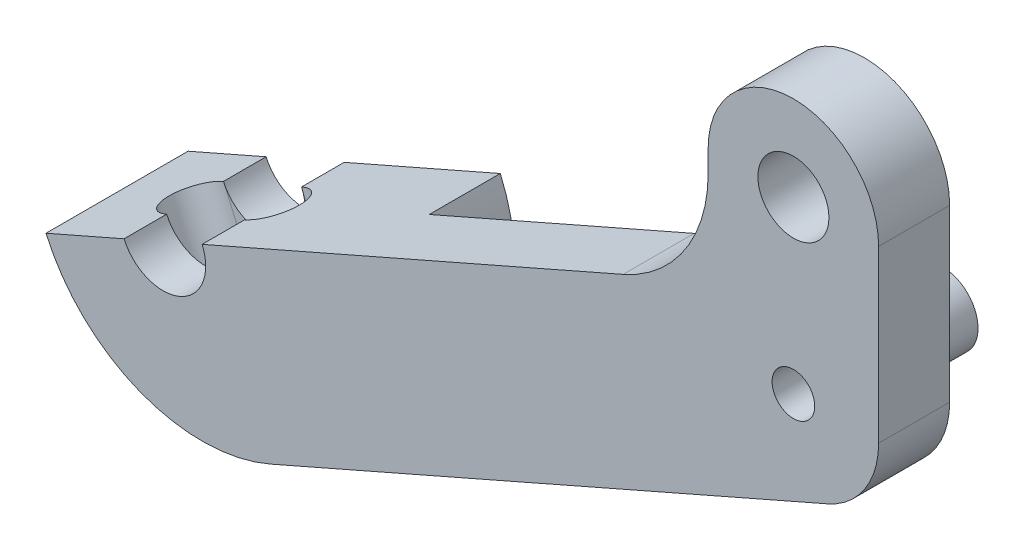
SolidWorks part; units mm, degrees
ref_plane "Plano frontal" through (0, 0, 0) normal (0, 0, 1) x (1, 0, 0)
ref_plane "Plano superior" through (0, 0, 0) normal (0, 1, 0) x (1, 0, 0)
ref_plane "Plano direito" through (0, 0, 0) normal (1, 0, 0) x (0, 0, -1)
sketch "Esboço7" plane through (0, 0, 0) normal (0, 0, 1) x (1, 0, 0)
  line L0 (0, 0) -> (0, -12) construction
  line L1 (6, 0) -> (6, -12)
  line L2 (-52.6179, -28.507) -> (-47.1224, -26.0988)
  line L3 (0, 0) -> (-6, -2.6293) construction
  line L5 (-6, -1.5426) -> (-6, 0)
  line L6 (-41.6269, -23.6906) -> (-11.9863, -10.7018)
  line L9 (2.4082, -17.4955) -> (-36.8105, -34.6816)
  line L10 (-43.9697, -25.8189) -> (-39.5583, -35.8857) construction
  circle A0 centre (0, 0) radius 2.5
  arc A1 (2.4082, -17.4955) -> (6, -12) centre (0, -12) ccw
  arc A2 (6, 0) -> (-6, 0) centre (0, 0) ccw
  arc A3 (-47.1224, -26.0988) -> (-41.6269, -23.6906) centre (-44.3747, -24.8947) ccw
  arc A5 (-6, -1.5426) -> (-11.9863, -10.7018) centre (-16, -1.5426) cw
  arc A6 (-52.6179, -28.507) -> (-36.8105, -34.6816) centre (-41.6269, -23.6906) ccw
  point P4 (0, -6)
  dimension "D1" = 12
  dimension "D2" = 10
extrude "Ressalto-extrusão1" add sketch "Esboço7" along normal blind 5
sketch "Esboço8" plane through (0, 0, 0) normal (0, 0, -1) x (-1, 0, 0)
  circle A0 centre (0, -12) radius 2.5
extrude "Ressalto-extrusão2" add sketch "Esboço8" along normal blind 5.5
sketch "Esboço9" plane through (0, 0, -5.5) normal (0, 0, -1) x (-1, 0, 0)
  circle A0 centre (0, -12) radius 1.5
extrude "Corte-extrusão4" cut sketch "Esboço9" against normal blind 25
sketch "Esboço10" plane through (0, 0, 0) normal (0, 0, -1) x (-1, 0, 0)
  line L0 (41.6269, -23.6906) -> (30.6359, -18.8742)
  line L1 (47.1224, -26.0988) -> (52.6179, -28.507)
  arc A0 (30.6359, -18.8742) -> (52.6179, -28.507) centre (41.6269, -23.6906) ccw
  arc A1 (41.6269, -23.6906) -> (47.1224, -26.0988) centre (44.3747, -24.8947) ccw
extrude "Ressalto-extrusão3" add sketch "Esboço10" along normal blind 5
sketch "Esboço11" plane through (6.8196, -15.5624, 0) normal (0.4014, -0.9159, 0) x (0.9159, 0.4014, 0)
  line L0 (-47.6354, 0) -> (-53.6354, 0) construction
  line L1 (-47.6354, 5) -> (-47.6354, -5) construction
  line L2 (-53.6354, 5) -> (-53.6354, -5) construction
  line L3 (-47.6354, -2) -> (-53.6354, -2)
  line L4 (-47.6354, 2) -> (-53.6354, 2)
  arc A0 (-47.6354, -2) -> (-47.6354, 2) centre (-47.6354, 0) ccw
  arc A1 (-53.6354, 2) -> (-53.6354, -2) centre (-53.6354, 0) ccw
  point P6 (-50.6354, 0)
extrude "Corte-extrusão5" cut sketch "Esboço11" against normal blind 16
sketch "Sketch1" plane through (0, 0, 0) normal (0, 0, -1) x (-1, 0, 0)
  circle A0 centre (0, -12) radius 3.5
  circle A1 centre (0, -12) radius 2.5
extrude "Boss-Extrude1" add sketch "Sketch1" along normal blind 0.5
